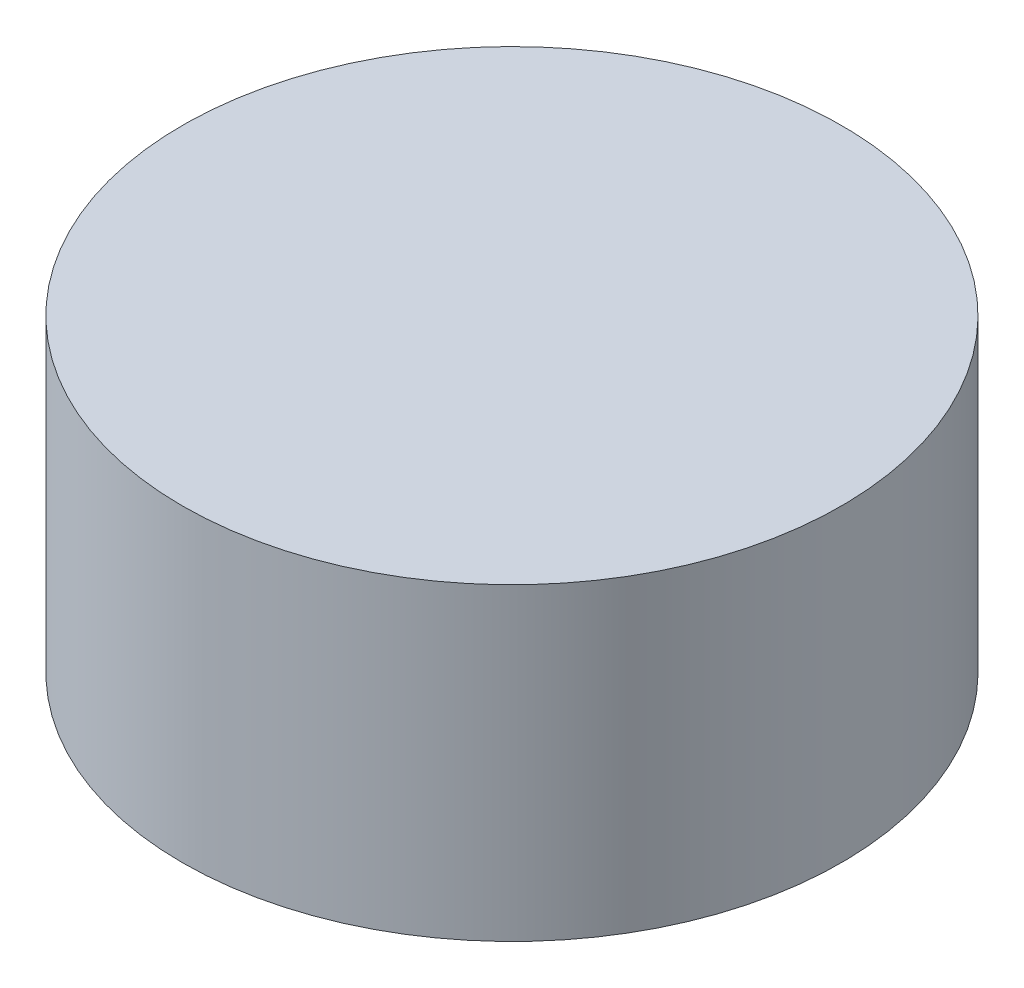
SolidWorks part; units mm, degrees
ref_plane "Front Plane" through (0, 0, 0) normal (0, 0, 1) x (1, 0, 0)
ref_plane "Top Plane" through (0, 0, 0) normal (0, 1, 0) x (1, 0, 0)
ref_plane "Right Plane" through (0, 0, 0) normal (1, 0, 0) x (0, 0, -1)
other "Configuration Table"
sketch "Sketch1" plane through (0, 0, 0) normal (0, 1, 0) x (1, 0, 0)
  circle A0 centre (0, 0) radius 16
extrude "KOLA1L_kapak_D32" add sketch "Sketch1" along normal blind 15 from offset 265 separate body
